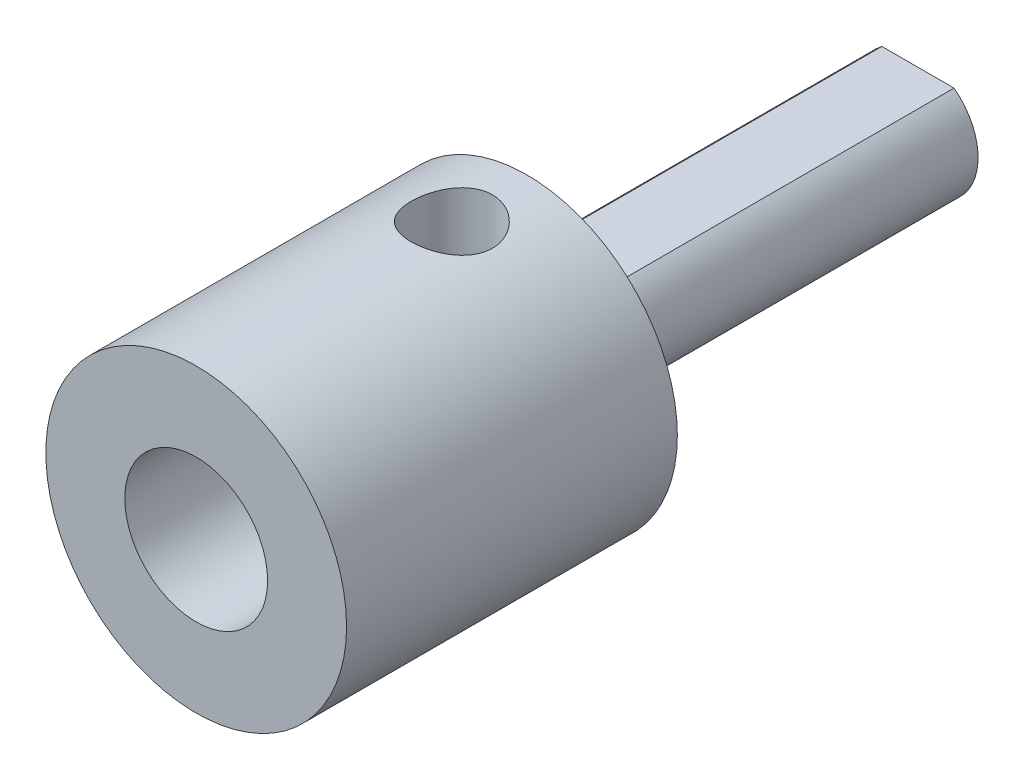
SolidWorks part; units mm, degrees
ref_plane "Front Plane" through (0, 0, 0) normal (0, 0, 1) x (1, 0, 0)
ref_plane "Top Plane" through (0, 0, 0) normal (0, 1, 0) x (1, 0, 0)
ref_plane "Right Plane" through (0, 0, 0) normal (1, 0, 0) x (0, 0, -1)
sketch "Sketch1" plane through (0, 0, 0) normal (0, 0, 1) x (1, 0, 0)
  circle A0 centre (0, 0) radius 5
  dimension "D1" = 10
extrude "Boss-Extrude1" add sketch "Sketch1" along normal blind 11
sketch "Sketch2" plane through (0, 0, 11) normal (0, 0, 1) x (1, 0, 0)
  circle A0 centre (0, 0) radius 2.375
  dimension "D1" = 4.75
sketch "Sketch3" plane through (0, 0, 0) normal (0, 0, -1) x (-1, 0, 0)
  line L0 (-1.2, 1.6) -> (1.2, 1.6)
  circle A0 centre (0, 0) radius 2
  dimension "D1" = 4
  dimension "D2" = 1.6
extrude "Cut-Extrude1" cut sketch "Sketch2" against normal blind 4
extrude "Boss-Extrude2" add sketch "Sketch3" along normal blind 13 contours L0 A0
ref_plane "Plane1" through (0, 5, 0) normal (0, 1, 0) x (1, 0, 0)
hole_wizard "#6-32 Tapped Hole2" positions "Sketch9" profile "Sketch10" tap size "#6-32" standard "ANSI Inch" end condition through all
sketch "Sketch9" plane through (0, 5, 0) normal (0, 1, 0) x (1, 0, 0)
  line L0 (5, 0) -> (-5, 0) construction
  point P0 (0, -2.5)
  dimension "D1" = 2.5
sketch "Sketch10" plane through (0, 5, 2.5) normal (1, 0, 0) x (0, 0, 1)
  line L0 (0, 0) -> (0, 10)
  line L1 (0, 10) -> (1.3525, 10)
  line L2 (1.3525, 10) -> (1.3525, 0)
  line L5 (1.3525, 0) -> (0, 0)
  line L11 (0, -6.35) -> (0, 107.95) construction
  dimension "Thru Tap Drill Dia." = 2.7051
  dimension "Thru Tap Drill Depth" = 10
cosmetic thread "Hole Thread2" parameters "D2"=3.5052
